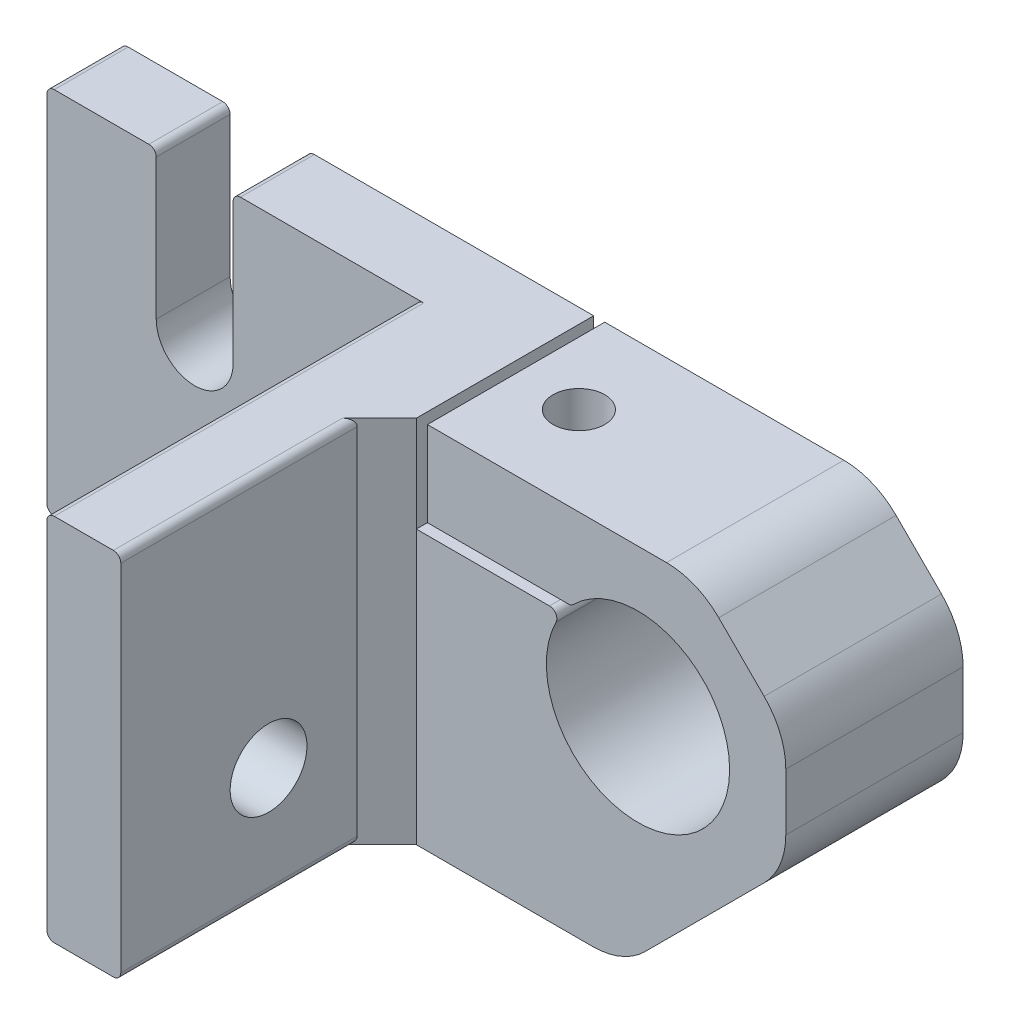
SolidWorks part; units mm, degrees
ref_plane "XY" through (0, 0, 0) normal (0, 0, 1) x (1, 0, 0)
ref_plane "XZ" through (0, 0, 0) normal (0, 1, 0) x (1, 0, 0)
ref_plane "YZ" through (0, 0, 0) normal (1, 0, 0) x (0, 0, -1)
sketch "Sketch1" plane through (0, 0, 0) normal (0, 0, 1) x (1, 0, 0)
  line L0 (-22.5, 12.5) -> (-28.5, 6.5)
  line L1 (-28.5, -12.5) -> (-17.5, -12.5) construction
  line L2 (-28.5, -12.5) -> (-28.5, -1.5) construction
  line L3 (-28.5, 12.5) -> (-5.7, 12.5) construction
  line L4 (28.5, -12.5) -> (28.5, 12.5)
  line L5 (-28.5, -12.5) -> (28.5, 12.5) construction
  line L6 (-28.5, 12.5) -> (28.5, -12.5) construction
  line L7 (28.5, -12.5) -> (-28.5, -12.5) construction
  line L8 (28.5, -12.5) -> (28.5, 12.5) construction
  line L9 (28.5, 12.5) -> (-28.5, 12.5) construction
  line L10 (-28.5, -12.5) -> (-28.5, 12.5) construction
  line L11 (28.5, -12.5) -> (-28.5, 12.5) construction
  line L12 (28.5, 12.5) -> (-28.5, -12.5) construction
  line L13 (-13.9859, 6.75) -> (-4.25, 6.75)
  line L14 (-28.5, 6.5) -> (-28.5, 12.5) construction
  line L15 (-17.5, -12.5) -> (-28.5, -1.5)
  line L16 (-5.7, 12.5) -> (-4.25, 12.5)
  line L17 (-28.5, 6.5) -> (-28.5, 12.5) construction
  line L18 (-28.5, -1.5) -> (-28.5, 6.5)
  line L19 (-17.5, -12.5) -> (28.5, -12.5)
  line L20 (-4.25, 6.75) -> (-4.25, 12.5)
  line L21 (-13.3824, 6) -> (-3.5, 6)
  line L22 (-3.5, 6) -> (-3.5, 12.5)
  line L23 (-13.9859, 6) -> (-3.5, 6) construction
  line L24 (-4.25, 12.5) -> (-3.5, 12.5) construction
  line L25 (-3.5, 12.5) -> (28.5, 12.5)
  line L26 (-22.5, 12.5) -> (-5.7, 12.5)
  arc A0 (-13.9859, 6.75) -> (-13.3824, 6) centre (-18.5, 2.5) ccw
  arc A1 (-13.3824, 6) -> (-13.9859, 6.75) centre (-18.5, 2.5) ccw construction
  point P0 (0, 0)
  point P5 (0, 0)
  dimension "D10" = 18.5
  dimension "D12" = 12.4
  dimension "D1" = 57
  dimension "D2" = 25
  dimension "D3" = 25
  dimension "D4" = 45
  dimension "D5" = 6
  dimension "D6" = 45
  dimension "D7" = 0.75
  dimension "D9" = 11
  dimension "D11" = 2.5
  dimension "D13" = 3.5
  dimension "D14" = 6
extrude "Boss-Extrude1" add sketch "Sketch1" along normal blind 12
sketch "Sketch3" plane through (0, 0, 12) normal (0, 0, 1) x (1, 0, 0)
  line L0 (-17.5, -12.5) -> (28.5, -12.5) construction
  line L1 (28.5, 12.5) -> (3.5, 12.5)
  line L2 (28.5, 12.5) -> (28.5, -12.5)
  line L3 (28.5, -12.5) -> (3.5, -12.5)
  line L4 (3.5, 12.5) -> (3.5, -12.5)
  dimension "D1" = 25
extrude "Cut-Extrude1" cut sketch "Sketch3" against normal blind 7
sketch "Sketch4" plane through (3.5, 0, 0) normal (1, 0, 0) x (0, 0, -1)
  line L0 (0, -12.5) -> (0, 12.5) construction
  line L1 (-12, 12.5) -> (-30, 12.5)
  line L2 (-12, 12.5) -> (-12, -12.5)
  line L3 (-12, -12.5) -> (-30, -12.5)
  line L4 (-30, 12.5) -> (-30, -12.5)
  line L5 (-5, -12.5) -> (-12, -12.5) construction
  circle A0 centre (-20, -5) radius 2.6
  dimension "D2" = 5.2
  dimension "D1" = 30
  dimension "D3" = 5
  dimension "D4" = 20
extrude "Boss-Extrude2" add sketch "Sketch4" against normal blind 5
chamfer "Chamfer1" distance 2 angle 45 1 edges
sketch "Sketch5" plane through (0, 0, 5) normal (0, 0, 1) x (1, 0, 0)
  line L0 (15.9, 2.5) -> (15.9, 12.5)
  line L1 (28.5, 12.5) -> (3.5, 12.5) construction
  line L2 (15.9, 12.5) -> (21.1, 12.5)
  line L3 (21.1, 12.5) -> (21.1, 2.5)
  arc A0 (15.9, 2.5) -> (21.1, 2.5) centre (18.5, 2.5) ccw
  dimension "D1" = 5.2
  dimension "D2" = 2.5
  dimension "D3" = 18.5
extrude "Cut-Extrude2" cut sketch "Sketch5" against normal blind 5
fillet "Fillet1" radius 5 4 edges at (-17.5, -12.5, 6) (-28.5, -1.5, 6) (-28.5, 6.5, 6) (-22.5, 12.5, 6)
fillet "Fillet2" radius 0.5 10 edges at (21.1, 12.5, 2.5) (15.9, 12.5, 2.5) (28.5, -12.5, 2.5) (28.5, 12.5, 2.5) (-13.3824, 6, 6) (-13.9859, 6.75, 6) (3.5, 12.5, 17.5) (3.5, -12.5, 17.5)
ref_plane "Plane1" through (0, 0, 6) normal (0, 0, -1) x (-1, 0, 0)
sketch "Sketch6" plane through (0, 0, 6) normal (0, 0, -1) x (-1, 0, 0)
  line L0 (8.5, 12.5) -> (8.5, -12.5) construction
  line L1 (4.25, 12.5) -> (20.4289, 12.5) construction
  line L2 (15.4289, -12.5) -> (-28, -12.5) construction
  line L3 (8.5, 12.5) -> (10.25, 12.5)
  line L4 (10.25, 12.5) -> (10.25, -7.5)
  line L5 (10.25, -7.5) -> (10.85, -7.5)
  line L6 (10.85, -7.5) -> (10.85, -12)
  line L7 (10.85, -12) -> (11, -12)
  line L8 (11, -12) -> (11, -12.5)
  line L9 (11, -12.5) -> (8.5, -12.5)
  line L10 (8.5, -12.5) -> (8.5, 12.5)
  dimension "D1" = 8.5
  dimension "D2" = 1.75
  dimension "D3" = 2.5
  dimension "D4" = 0.15
  dimension "D5" = 0.5
  dimension "D6" = 5
revolve "Cut-Revolve1" cut sketch "Sketch6" angle 360 about L0
mirror "Mirror1" about plane through (0, 0, 0) normal (1, 0, 0) of bodies 130
delete or keep bodies "Body-Delete1" bodies 130
